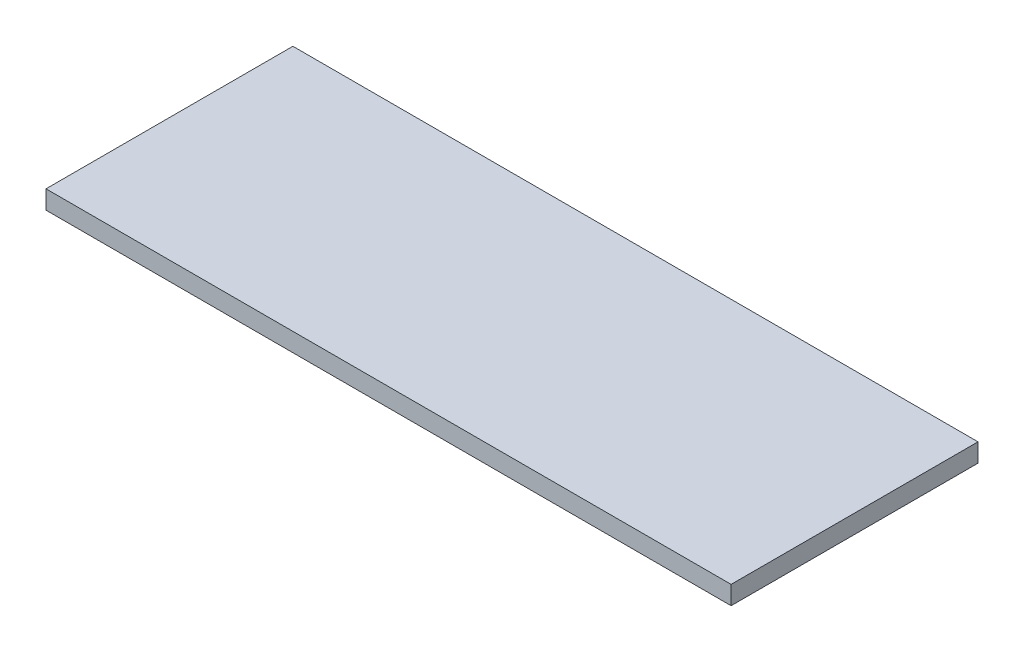
SolidWorks part; units mm, degrees
ref_plane "Front Plane" through (0, 0, 0) normal (0, 0, 1) x (1, 0, 0)
ref_plane "Top Plane" through (0, 0, 0) normal (0, 1, 0) x (1, 0, 0)
ref_plane "Right Plane" through (0, 0, 0) normal (1, 0, 0) x (0, 0, -1)
sketch "Sketch1" plane through (0, 0, 0) normal (0, 0, 1) x (1, 0, 0)
  line L1 (88, -1.5) -> (199, -1.5)
  line L2 (88, -1.5) -> (88, 1.5)
  line L3 (88, 1.5) -> (199, 1.5)
  line L4 (199, -1.5) -> (199, 1.5)
extrude "Plate" add sketch "Sketch1" along normal blind 40
